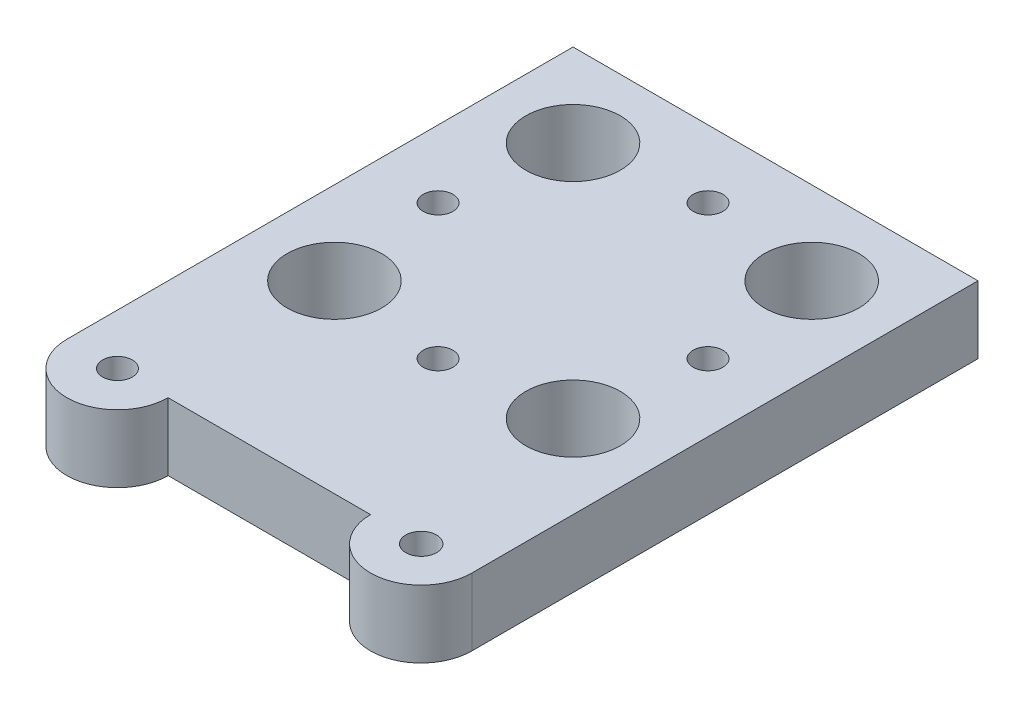
SolidWorks part; units mm, degrees
material "ABS"
ref_plane "Front Plane" through (0, 0, 0) normal (0, 0, 1) x (1, 0, 0)
ref_plane "Top Plane" through (0, 0, 0) normal (0, 1, 0) x (1, 0, 0)
ref_plane "Right Plane" through (0, 0, 0) normal (1, 0, 0) x (0, 0, -1)
sketch "草图1" plane through (0, 0, 0) normal (0, 1, 0) x (1, 0, 0)
  line L1 (-30, 30) -> (30, 30)
  line L2 (-30, 30) -> (-30, -30)
  line L3 (-30, -30) -> (30, -30)
  line L4 (30, 30) -> (30, -30)
  line L5 (-30, 30) -> (30, -30) construction
  line L6 (-30, -30) -> (30, 30) construction
  point P0 (0, 0)
extrude "凸台-拉伸1" add sketch "草图1" along normal blind 10
sketch "草图2" plane through (0, 10, 0) normal (0, 1, 0) x (1, 0, 0)
  line L0 (-30, 30) -> (30, -30)
  circle A0 centre (0, 0) radius 20
  circle A1 centre (0, 20) radius 2.2
  circle A2 centre (-20, 0) radius 2.2
  circle A3 centre (0, -20) radius 2.2
  circle A4 centre (20, 0) radius 2.2
extrude "切除-拉伸1" cut sketch "草图2" against normal blind 10 contours A0 A2 | A0 A2 | A0 A3 | A0 A3 | A0 A4 | A0 A4 | A0 A1 | A0 A1
sketch "草图3" plane through (0, 0, 0) normal (0, -1, 0) x (1, 0, 0)
  line L1 (4, 20) -> (2, 23.4641)
  line L2 (2, 23.4641) -> (-2, 23.4641)
  line L3 (-2, 23.4641) -> (-4, 20)
  line L4 (-4, 20) -> (-2, 16.5359)
  line L5 (-2, 16.5359) -> (2, 16.5359)
  line L6 (2, 16.5359) -> (4, 20)
  line L7 (-16, 0) -> (-18, 3.4641)
  line L8 (-18, 3.4641) -> (-22, 3.4641)
  line L9 (-22, 3.4641) -> (-24, 0)
  line L10 (-24, 0) -> (-22, -3.4641)
  line L11 (-22, -3.4641) -> (-18, -3.4641)
  line L12 (-18, -3.4641) -> (-16, 0)
  line L13 (24, 0) -> (22, 3.4641)
  line L14 (22, 3.4641) -> (18, 3.4641)
  line L15 (18, 3.4641) -> (16, 0)
  line L16 (16, 0) -> (18, -3.4641)
  line L17 (18, -3.4641) -> (22, -3.4641)
  line L18 (22, -3.4641) -> (24, 0)
  line L19 (4, -20) -> (2, -16.5359)
  line L20 (2, -16.5359) -> (-2, -16.5359)
  line L21 (-2, -16.5359) -> (-4, -20)
  line L22 (-4, -20) -> (-2, -23.4641)
  line L23 (-2, -23.4641) -> (2, -23.4641)
  line L24 (2, -23.4641) -> (4, -20)
  circle A0 centre (0, 20) radius 4 construction
  circle A1 centre (-20, 0) radius 4 construction
  circle A2 centre (20, 0) radius 4 construction
  circle A3 centre (0, -20) radius 4 construction
extrude "切除-拉伸2" cut sketch "草图3" against normal blind 3.5
sketch "草图4" plane through (0, 0, 0) normal (0, -1, 0) x (1, 0, 0)
  line L0 (-17.6777, 17.6777) -> (17.6777, -17.6777)
  line L1 (-17.6777, -17.6777) -> (17.6777, 17.6777)
  circle A0 centre (0, 0) radius 25
  circle A1 centre (-17.6777, 17.6777) radius 7
  circle A2 centre (-17.6777, -17.6777) radius 7
  circle A3 centre (17.6777, -17.6777) radius 7
  circle A4 centre (17.6777, 17.6777) radius 7
extrude "切除-拉伸3" cut sketch "草图4" against normal through all contours A0 A1 L0 | L0 A1 A0 | A0 A2 | A0 A2 L1 | L1 A2 A0 | A0 A1 | L1 A4 A0 | A0 A4 L1 | A0 A4 | A0 A3 L0 | L0 A3 A0 | A0 A3
sketch "草图5" plane through (0, 0, 30) normal (0, 0, 1) x (1, 0, 0)
  line L1 (-30, 10) -> (30, 10)
  line L2 (-30, 10) -> (-30, 0)
  line L3 (-30, 0) -> (30, 0)
  line L4 (30, 10) -> (30, 0)
extrude "凸台-拉伸2" add sketch "草图5" along normal blind 15
sketch "草图6" plane through (0, 10, 0) normal (0, 1, 0) x (1, 0, 0)
  line L0 (-30, 30) -> (-30, -45) construction
  line L1 (30, -45) -> (-30, -45)
  line L2 (30, -45) -> (30, -30)
  line L3 (30, -30) -> (-30, -30)
  line L4 (-30, -45) -> (-30, -30)
  circle A0 centre (0, -45) radius 22.5
  circle A1 centre (22.5, -45) radius 2.2
  circle A2 centre (-22.5, -45) radius 2.2
  circle A3 centre (22.5, -45) radius 7.5
  circle A4 centre (-22.5, -45) radius 7.5
  line M17 (-30, -45) -> (30, -45)
extrude "凸台-拉伸3" add sketch "草图6" against normal up to surface (10 mm away) contours A0 A4 A2 M17 | A4 A0 A2 M17 | A4 A0 A2 M17 | A0 A4 A2 M17 | L1 A3 A0 A1 | A0 A3 L1 A1 | L1 A3 A0 A1 | A0 A3 L1 A1 up to face at (17.6777, 0, -24.6777)
sketch "草图7" plane through (0, 10, 0) normal (0, 1, 0) x (1, 0, 0)
  line L0 (24.7, -45) -> (20.3, -45) construction
  line L1 (-20.3, -45) -> (-24.7, -45) construction
  circle A0 centre (22.5, -45) radius 2.2781
  circle A1 centre (-22.5, -45) radius 2.2
extrude "切除-拉伸4" cut sketch "草图7" against normal through all
sketch "草图8" plane through (0, 0, 0) normal (0, -1, 0) x (-1, 0, 0)
  circle A0 centre (-22.5, -45) radius 4
  circle A1 centre (22.5, -45) radius 4
extrude "切除-拉伸5" cut sketch "草图8" against normal blind 4
